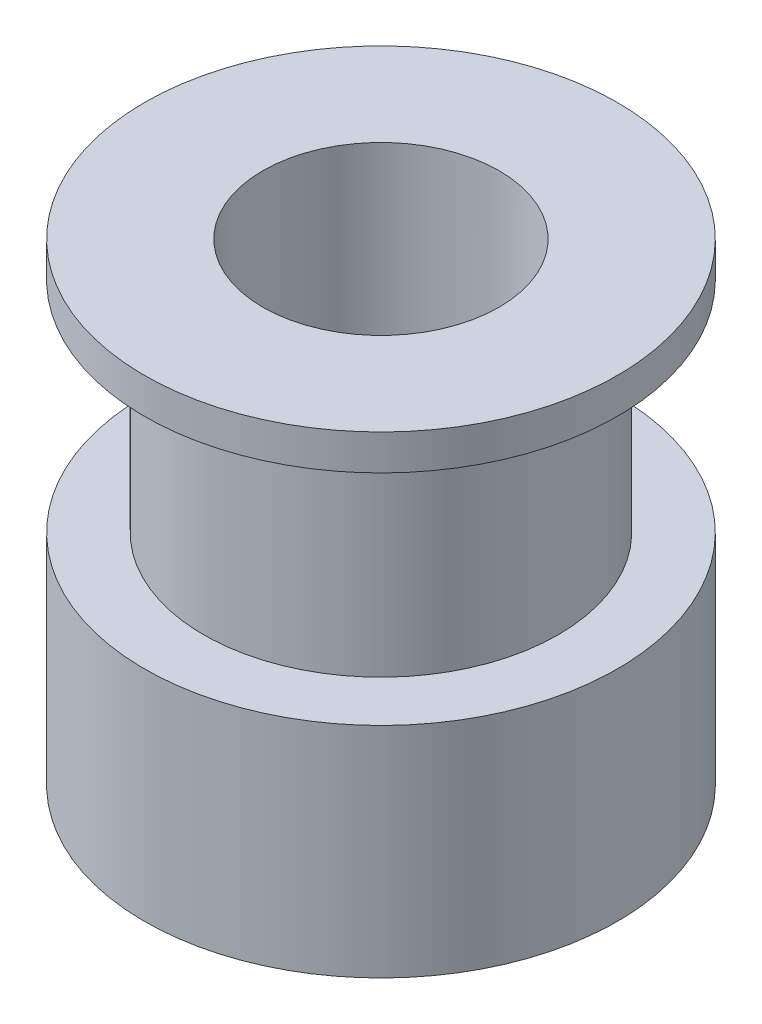
SolidWorks part; units mm, degrees
ref_plane "Front Plane" through (0, 0, 0) normal (0, 0, 1) x (1, 0, 0)
ref_plane "Top Plane" through (0, 0, 0) normal (0, 1, 0) x (1, 0, 0)
ref_plane "Right Plane" through (0, 0, 0) normal (1, 0, 0) x (0, 0, -1)
sketch "Sketch1" plane through (0, 0, 0) normal (0, 0, 1) x (1, 0, 0)
  line L0 (0, 1004.7764) -> (0, 5) construction
  line L1 (0, -11) -> (0, -1018.6139) construction
  line L2 (0, 5) -> (-8, 5)
  line L4 (-6, 3.8) -> (-8, 3.8)
  line L5 (-8, 5) -> (-8, 3.8)
  line L7 (-6, 3.8) -> (-6, -3.6)
  line L10 (-6, -3.6) -> (-8, -3.6)
  line L12 (0, -11) -> (-8, -11)
  line L13 (-8, -3.6) -> (-8, -11)
  line L14 (0, 5) -> (0, -11)
  dimension "D1" = 7.4
  dimension "D2" = 16
  dimension "D3" = 7.4
  dimension "D4" = 8
  dimension "D5" = 8
  dimension "D6" = 6
  dimension "D7" = 5
revolve "Revolve1" add sketch "Sketch1" angle 360 about L0
sketch "Sketch2" plane through (0, 5, 0) normal (0, 1, 0) x (1, 0, 0)
  circle A0 centre (0, 0) radius 4
  dimension "D1" = 8
extrude "Cut-Extrude1" cut sketch "Sketch2" against normal up to next
sketch "Sketch3" plane through (0, 0, 0) normal (0, 0, 1) x (1, 0, 0)
  line L0 (0, 0) -> (0, -6.4964) construction
  line L1 (8, -3.6) -> (-8, -3.6) construction
  circle A0 centre (0, -7.3) radius 2
  dimension "D1" = 4
  dimension "D2" = 3.7
extrude "Cut-Extrude2" cut sketch "Sketch3" against normal up to next
pattern_circular "CirPattern1" count 2 every 90 about axis through (0, -11, 0) along (0, -1, 0) of "Cut-Extrude2"
